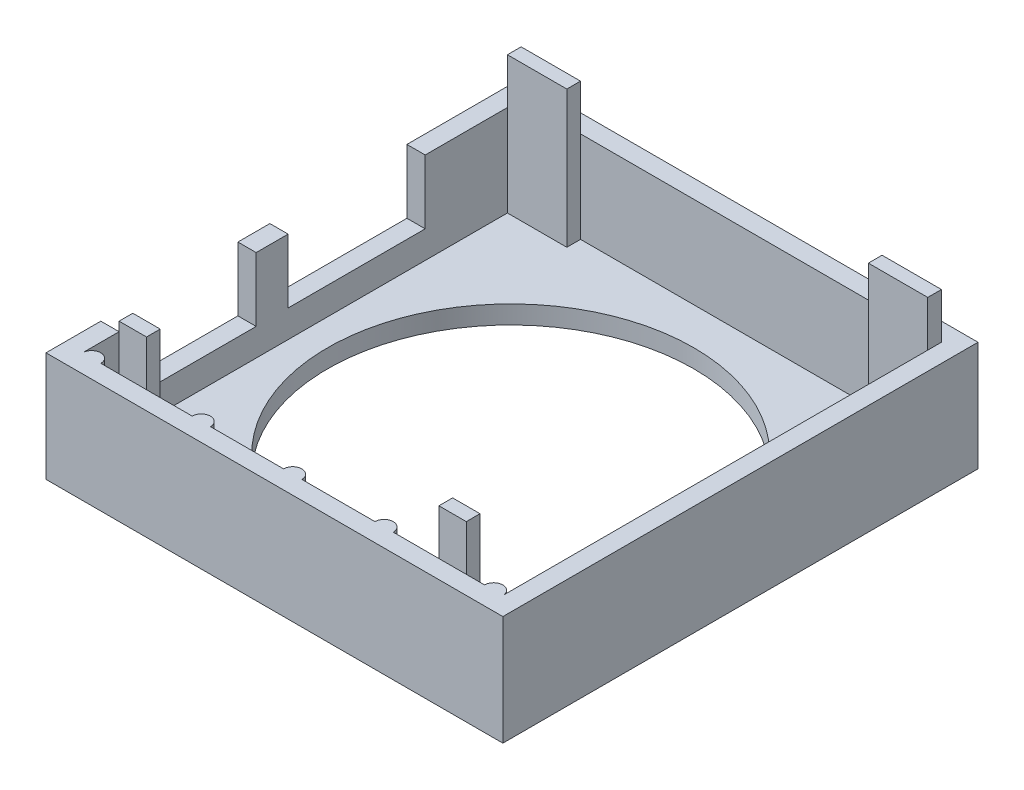
SolidWorks part; units mm, degrees
ref_plane "Front Plane" through (0, 0, 0) normal (0, 0, 1) x (1, 0, 0)
ref_plane "Top Plane" through (0, 0, 0) normal (0, 1, 0) x (1, 0, 0)
ref_plane "Right Plane" through (0, 0, 0) normal (1, 0, 0) x (0, 0, -1)
sketch "Sketch2" plane through (0, 0, 0) normal (0, 1, 0) x (1, 0, 0)
  line L1 (0, 0) -> (50, 0)
  line L2 (0, 0) -> (0, 52)
  line L3 (0, 52) -> (50, 52)
  line L4 (50, 0) -> (50, 52)
  dimension "D1" = 50
  dimension "D2" = 52
extrude "Boss-Extrude1" add sketch "Sketch2" along normal blind 12
sketch "Sketch5" plane through (0, 12, 0) normal (0, 1, 0) x (1, 0, 0)
  line L0 (0, 0) -> (50, 0) construction
  line L1 (2, 2) -> (48, 2)
  line L2 (2, 2) -> (2, 50)
  line L3 (2, 50) -> (48, 50)
  line L4 (48, 2) -> (48, 50)
  line L5 (0, 52) -> (0, 0) construction
  dimension "D1" = 46
  dimension "D2" = 2
  dimension "D3" = 2
  dimension "D4" = 48
extrude "Cut-Extrude1" cut sketch "Sketch5" against normal blind 10
sketch "Sketch7" plane through (0, 12, 0) normal (0, 1, 0) x (1, 0, 0)
  line L0 (2, 50) -> (2, 2) construction
  line L1 (2, 39.5) -> (0, 39.5)
  line L2 (2, 39.5) -> (2, 24.5)
  line L3 (2, 24.5) -> (0, 24.5)
  line L4 (0, 39.5) -> (0, 24.5)
  line L5 (0, 52) -> (0, 0) construction
  line L8 (0, 21) -> (2, 21)
  line L9 (0, 21) -> (0, 6)
  line L10 (0, 6) -> (2, 6)
  line L11 (2, 21) -> (2, 6)
  dimension "D1" = 10.5
  dimension "D2" = 15
  dimension "D3" = 3.5
  dimension "D4" = 15
extrude "Cut-Extrude2" cut sketch "Sketch7" against normal blind 7
sketch "Sketch10" plane through (0, 2, 0) normal (0, 1, 0) x (1, 0, 0)
  line L0 (2, 2) -> (48, 2) construction
  circle A0 centre (25, 2) radius 1
  circle A1 centre (35, 2) radius 1
  circle A2 centre (15, 2) radius 1
  circle A3 centre (3, 2) radius 1
  circle A4 centre (47, 2) radius 1
  dimension "D1" = 10
  dimension "D2" = 10
  dimension "D3" = 12
  dimension "D4" = 12
extrude "Boss-Extrude2" add sketch "Sketch10" along normal blind 10
sketch "Sketch11" plane through (0, 2, 0) normal (0, 1, 0) x (1, 0, 0)
  line L0 (4, 2) -> (14, 2) construction
  line L1 (6, 3.5) -> (9, 3.5)
  line L2 (6, 3.5) -> (6, 2)
  line L3 (6, 2) -> (9, 2)
  line L4 (9, 3.5) -> (9, 2)
  line L5 (2, 50) -> (2, 2) construction
  line L6 (36, 2) -> (46, 2) construction
  line L7 (44, 2) -> (41, 2)
  line L8 (44, 2) -> (44, 3.5)
  line L9 (44, 3.5) -> (41, 3.5)
  line L10 (41, 2) -> (41, 3.5)
  line L11 (48, 2) -> (48, 50) construction
  line L12 (48, 50) -> (2, 50) construction
  line L13 (2, 50) -> (8.5, 50)
  line L14 (2, 50) -> (2, 48.5004)
  line L15 (2, 48.5004) -> (8.5, 48.5004)
  line L16 (8.5, 50) -> (8.5, 48.5004)
  line L18 (41.5, 50) -> (48, 50)
  line L19 (41.5, 50) -> (41.5, 48.5004)
  line L20 (41.5, 48.5004) -> (48, 48.5004)
  line L21 (48, 50) -> (48, 48.5004)
  dimension "D1" = 4
  dimension "D2" = 1.5
  dimension "D3" = 4
  dimension "D4" = 3
  dimension "D5" = 33
  dimension "D6" = 6.5
  dimension "D7" = 6.5
  dimension "D8" = 6.5
extrude "Boss-Extrude3" add sketch "Sketch11" along normal blind 15
sketch "Sketch12" plane through (0, 2, 0) normal (0, 1, 0) x (1, 0, 0)
  circle A0 centre (24.9597, 25.8978) radius 20.034
extrude "Cut-Extrude4" cut sketch "Sketch12" against normal blind 15
